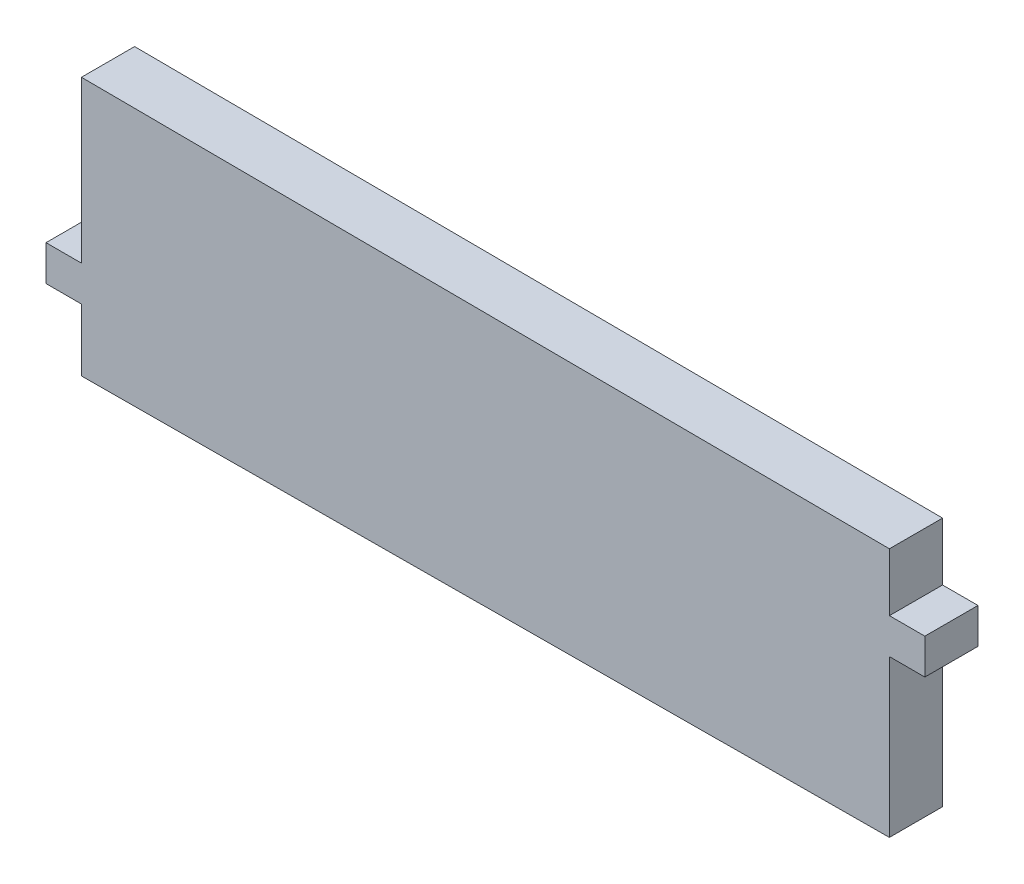
SolidWorks part; units mm, degrees
material "Balsa"
ref_plane "Front Plane" through (0, 0, 0) normal (0, 0, 1) x (1, 0, 0)
ref_plane "Top Plane" through (0, 0, 0) normal (0, 1, 0) x (1, 0, 0)
ref_plane "Right Plane" through (0, 0, 0) normal (1, 0, 0) x (0, 0, -1)
sketch "Sketch1" plane through (0, 0, 0) normal (0, 0, 1) x (1, 0, 0)
  line L0 (15.8059, -23.2864) -> (12.6309, -23.2864)
  line L1 (12.6309, -23.2864) -> (12.6309, -26.4614)
  line L2 (12.6309, -26.4614) -> (15.8059, -26.4614)
  line L3 (15.8059, -26.4614) -> (15.8059, -32.0433)
  line L4 (15.8059, -23.2864) -> (15.8059, -8.8652)
  line L5 (88.1959, -17.6222) -> (91.3709, -17.6222)
  line L6 (91.3709, -17.6222) -> (91.3709, -14.4472)
  line L7 (91.3709, -14.4472) -> (88.1959, -14.4472)
  line L8 (88.1959, -14.4472) -> (88.1959, -9.256)
  line L9 (88.1959, -17.6222) -> (88.1959, -31.6534)
  line L10 (88.1959, -31.6534) -> (15.8059, -32.0433)
  line L11 (15.8059, -8.8652) -> (88.1959, -9.256)
extrude "Boss-Extrude1" add sketch "Sketch1" along normal up to surface (4.7625 mm away)
